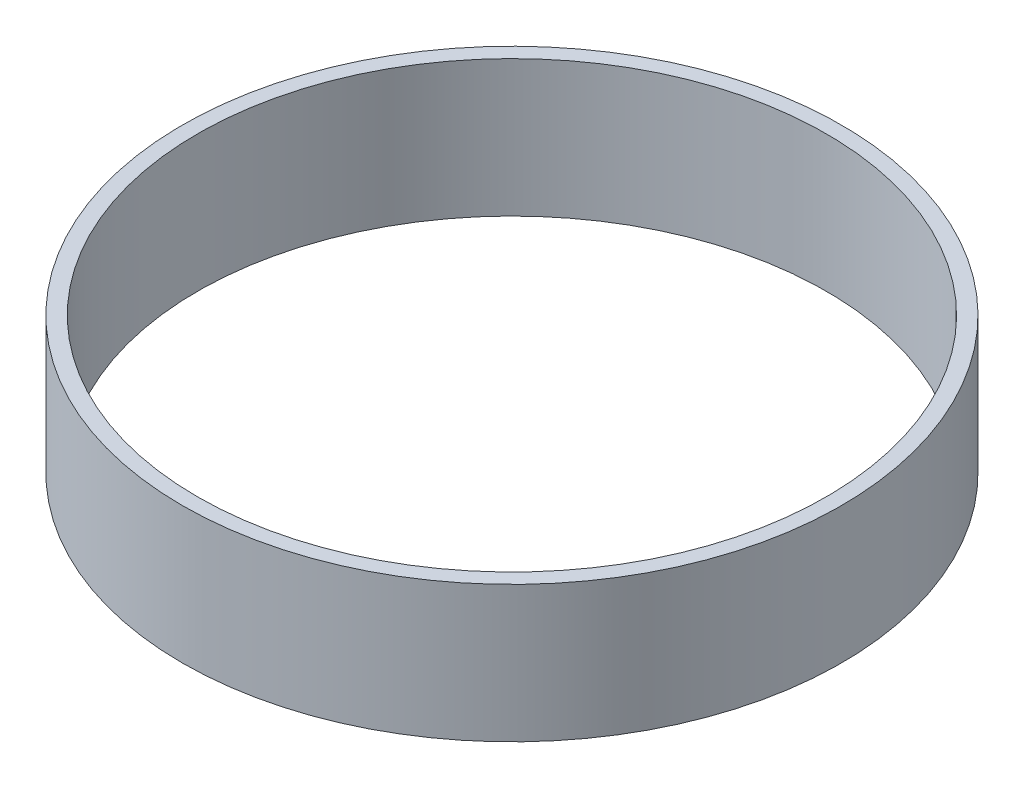
SolidWorks part; units mm, degrees
material "AISI 304"
ref_plane "Front Plane" through (0, 0, 0) normal (0, 0, 1) x (1, 0, 0)
ref_plane "Top Plane" through (0, 0, 0) normal (0, 1, 0) x (1, 0, 0)
ref_plane "Right Plane" through (0, 0, 0) normal (1, 0, 0) x (0, 0, -1)
sketch "Sketch1" plane through (0, 0, 0) normal (0, 1, 0) x (1, 0, 0)
  circle A0 centre (0, 0) radius 43.5
  circle A1 centre (0, 0) radius 41.5
  dimension "D1" = 87
  dimension "D2" = 2
extrude "Boss-Extrude1" add sketch "Sketch1" along normal blind 18
